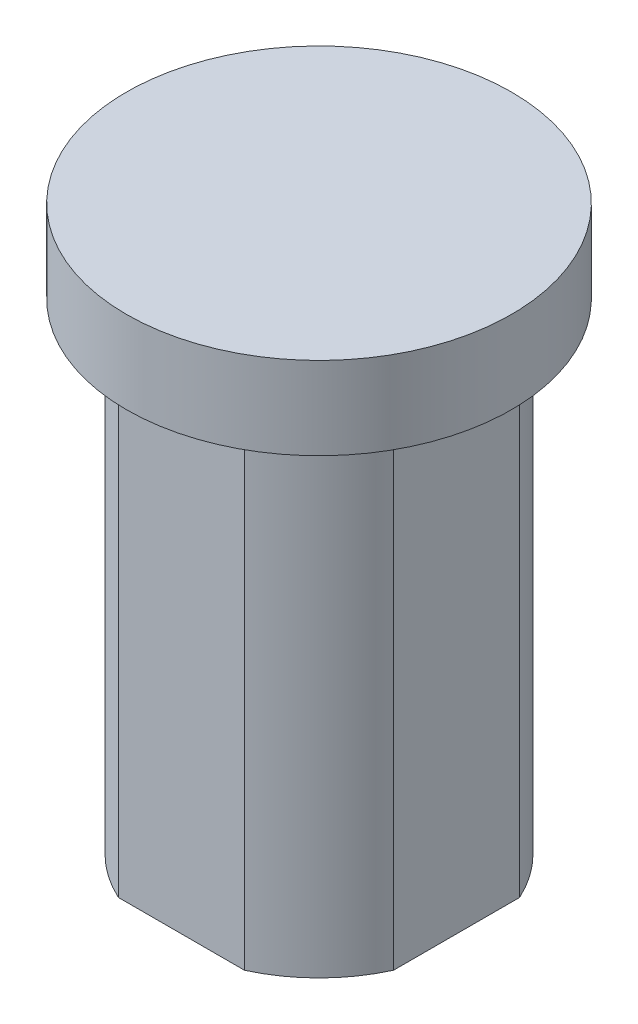
SolidWorks part; units mm, degrees
ref_plane "前视基准面" through (0, 0, 0) normal (0, 0, 1) x (1, 0, 0)
ref_plane "上视基准面" through (0, 0, 0) normal (0, 1, 0) x (1, 0, 0)
ref_plane "右视基准面" through (0, 0, 0) normal (1, 0, 0) x (0, 0, -1)
other "Configuration Table"
sketch "草图1" plane through (0, 0, 0) normal (0, 1, 0) x (1, 0, 0)
  line L1 (4.5826, -10) -> (-4.5826, -10)
  line L2 (10, -4.5826) -> (10, 4.5826)
  line L3 (4.5826, 10) -> (-4.5826, 10)
  line L4 (-10, -4.5826) -> (-10, 4.5826)
  line L5 (7.7782, -7.7782) -> (-7.7782, 7.7782) construction
  line L6 (7.7782, 7.7782) -> (-7.7782, -7.7782) construction
  arc A0 (-4.5826, 10) -> (-10, 4.5826) centre (0, 0) ccw
  arc A1 (-10, -4.5826) -> (-4.5826, -10) centre (0, 0) ccw
  arc A2 (4.5826, -10) -> (10, -4.5826) centre (0, 0) ccw
  arc A3 (10, 4.5826) -> (4.5826, 10) centre (0, 0) ccw
  dimension "D1" = 22
  dimension "D2" = 20
  dimension "D3" = 20
extrude "凸台-拉伸1" add sketch "草图1" along normal blind 35
sketch "草图2" plane through (0, 35, 0) normal (0, 1, 0) x (1, 0, 0)
  circle A0 centre (0, 0) radius 14
  dimension "D1" = 28
extrude "凸台-拉伸2" add sketch "草图2" along normal blind 6
